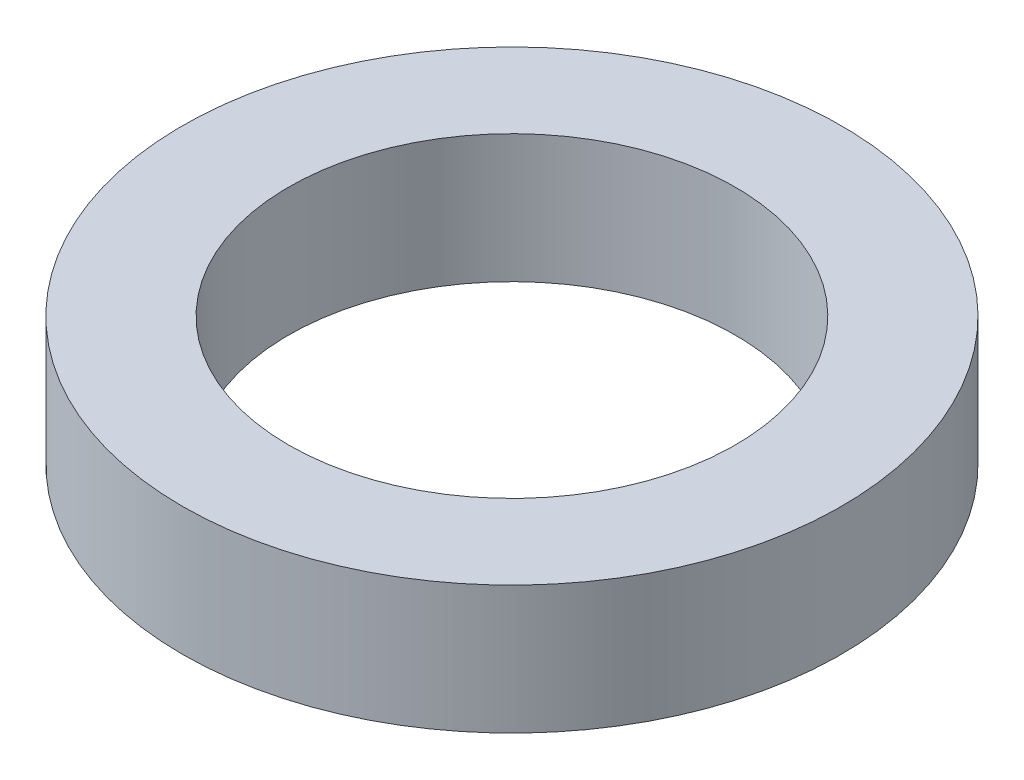
SolidWorks part; units mm, degrees
other "Outer Wheel Spacer"
ref_plane "Front Plane" through (0, 0, 0) normal (0, 0, 1) x (1, 0, 0)
ref_plane "Top Plane" through (0, 0, 0) normal (0, 1, 0) x (1, 0, 0)
ref_plane "Right Plane" through (0, 0, 0) normal (1, 0, 0) x (0, 0, -1)
sketch3d "Spacer stock sketch datum points"
  point P0 (-19.0092, -240.5, -53.2449)
  point P1 (-9.0092, -240.5, -53.2449)
  point P2 (-19.0092, -240.5, -63.2449)
ref_plane "Spacer stock sketch plane" through (0, -240.5, 0) normal (0, 1, 0) x (1, 0, 0)
sketch "Spacer stock sketch" plane through (0, -240.5, 0) normal (0, 1, 0) x (1, 0, 0)
  circle A0 centre (-19.0092, 53.2449) radius 9
extrude "Spacer stock" add sketch "Spacer stock sketch" along normal blind 3.5 separate body
sketch3d "Axle running clearance sketch datum points"
  point P0 (-19.0092, -240.6, -53.2449)
  point P1 (-9.0092, -240.6, -53.2449)
  point P2 (-19.0092, -240.6, -63.2449)
ref_plane "Axle running clearance sketch plane" through (0, -240.6, 0) normal (0, 1, 0) x (1, 0, 0)
sketch "Axle running clearance sketch" plane through (0, -240.6, 0) normal (0, 1, 0) x (1, 0, 0)
  circle A0 centre (-19.0092, 53.2449) radius 6.1
extrude "Axle running clearance" cut sketch "Axle running clearance sketch" along normal blind 3.7
